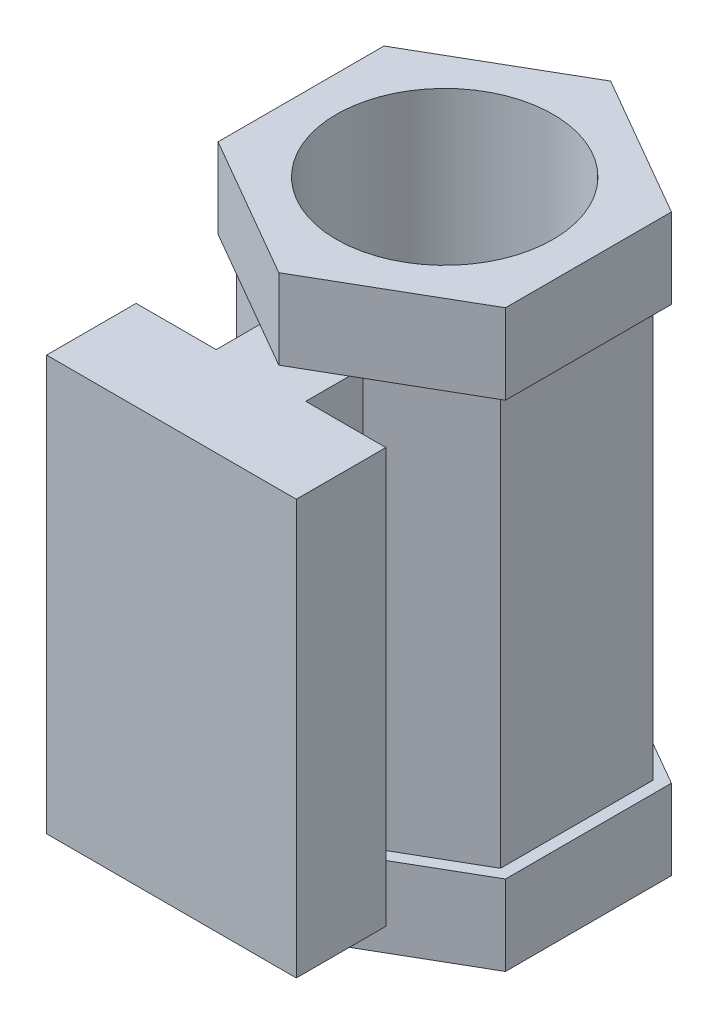
SolidWorks part; units mm, degrees
ref_plane "Спереди" through (0, 0, 0) normal (0, 0, 1) x (1, 0, 0)
ref_plane "Сверху" through (0, 0, 0) normal (0, 1, 0) x (1, 0, 0)
ref_plane "Справа" through (0, 0, 0) normal (1, 0, 0) x (0, 0, -1)
sketch "Эскиз центра" plane through (0, 0, 0) normal (0, 1, 0) x (1, 0, 0)
  line L0 (0, 0) -> (0, -290) construction
  line L1 (0, 161.6581) -> (-140, 80.829)
  line L2 (-140, 80.829) -> (-140, -80.829)
  line L3 (-140, -80.829) -> (-47.5, -134.2339)
  line L4 (47.5, -134.2339) -> (140, -80.829)
  line L5 (140, -80.829) -> (140, 80.829)
  line L6 (140, 80.829) -> (0, 161.6581)
  line L7 (132.5, -290) -> (-132.5, -290)
  line L8 (-132.5, -290) -> (-132.5, -195)
  line L9 (-132.5, -195) -> (-47.5, -195)
  line L10 (-47.5, -195) -> (-47.5, -134.2339)
  line L11 (47.5, -195) -> (47.5, -134.2339)
  line L12 (132.5, -195) -> (47.5, -195)
  line L13 (132.5, -290) -> (132.5, -195)
  circle A0 centre (0, 0) radius 140 construction
sketch "Эскиз2" plane through (0, 0, 0) normal (0, 1, 0) x (1, 0, 0)
  line L1 (0, 176.0918) -> (-152.5, 88.0459)
  line L2 (-152.5, 88.0459) -> (-152.5, -88.0459)
  line L3 (-152.5, -88.0459) -> (0, -176.0918)
  line L4 (0, -176.0918) -> (152.5, -88.0459)
  line L5 (152.5, -88.0459) -> (152.5, 88.0459)
  line L6 (152.5, 88.0459) -> (0, 176.0918)
  circle A0 centre (0, 0) radius 152.5 construction
extrude "Боковой многогранник 1" add sketch "Эскиз2" along normal blind 85
extrude "Центральная часть" add sketch "Эскиз центра" against normal blind 440
sketch "Эскиз4" plane through (0, -440, 0) normal (0, -1, 0) x (1, 0, 0)
  line L1 (0, -176.0918) -> (152.5, -88.0459)
  line L2 (152.5, -88.0459) -> (152.5, 88.0459)
  line L3 (152.5, 88.0459) -> (0, 176.0918)
  line L4 (0, 176.0918) -> (-152.5, 88.0459)
  line L5 (-152.5, 88.0459) -> (-152.5, -88.0459)
  line L6 (-152.5, -88.0459) -> (0, -176.0918)
  circle A0 centre (0, 0) radius 152.5 construction
extrude "Боковой многогранник 2" add sketch "Эскиз4" along normal blind 85
sketch "Эскиз5" plane through (0, 85, 0) normal (0, 1, 0) x (1, 0, 0)
  circle A0 centre (0, 0) radius 115
extrude "Вырез-Вытянуть1" cut sketch "Эскиз5" against normal through all
sketch "Эскиз6" plane through (140, 0, 0) normal (1, 0, 0) x (0, 0, -1)
  circle A0 centre (0, -220) radius 85
